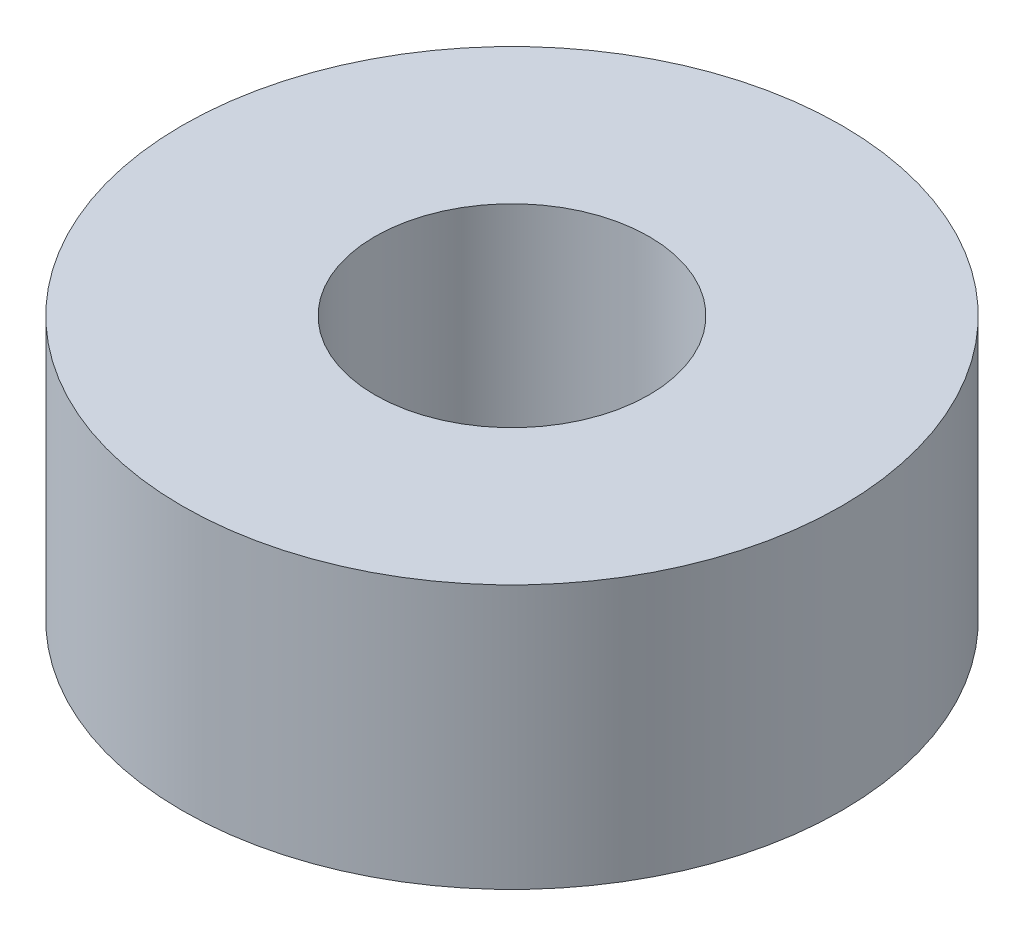
SolidWorks part; units mm, degrees
ref_plane "Front Plane" through (0, 0, 0) normal (0, 0, 1) x (1, 0, 0)
ref_plane "Top Plane" through (0, 0, 0) normal (0, 1, 0) x (1, 0, 0)
ref_plane "Right Plane" through (0, 0, 0) normal (1, 0, 0) x (0, 0, -1)
sketch "Sketch1" plane through (0, 0, 0) normal (0, 1, 0) x (1, 0, 0)
  circle A0 centre (0, 0) radius 3.302
  circle A1 centre (0, 0) radius 7.9375
  dimension "D1" = 6.604
  dimension "D2" = 15.875
extrude "Boss-Extrude1" add sketch "Sketch1" along normal blind 6.35
equation "\"0.26ib\"=0.26"
